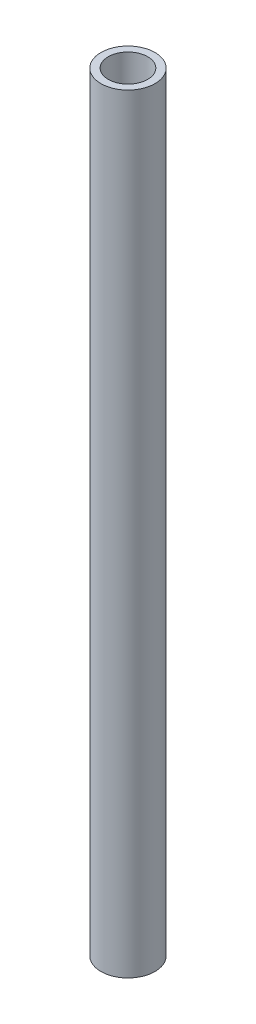
SolidWorks part; units mm, degrees
ref_plane "Front Plane" through (0, 0, 0) normal (0, 0, 1) x (1, 0, 0)
ref_plane "Top Plane" through (0, 0, 0) normal (0, 1, 0) x (1, 0, 0)
ref_plane "Right Plane" through (0, 0, 0) normal (1, 0, 0) x (0, 0, -1)
sketch "Sketch1" plane through (0, 0, 0) normal (0, 1, 0) x (1, 0, 0)
  circle A0 centre (0, 0) radius 3.1
  circle A1 centre (0, 0) radius 4.25
  dimension "D1" = 6.2
  dimension "D2" = 8.5
extrude "Boss-Extrude1" add sketch "Sketch1" along normal blind 121
